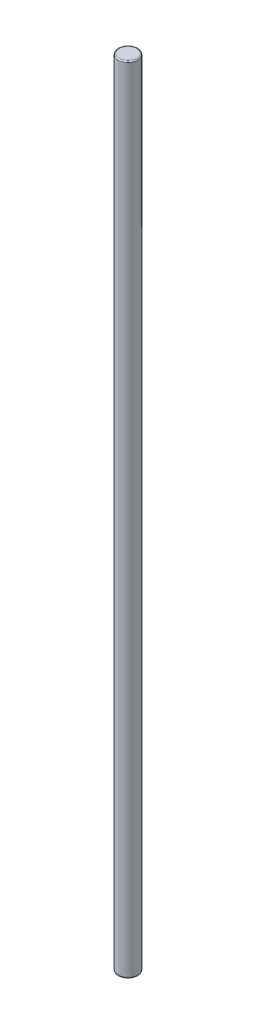
SolidWorks part; units mm, degrees
material "AISI 304"
ref_plane "Front Plane" through (0, 0, 0) normal (0, 0, 1) x (1, 0, 0)
ref_plane "Top Plane" through (0, 0, 0) normal (0, 1, 0) x (1, 0, 0)
ref_plane "Right Plane" through (0, 0, 0) normal (1, 0, 0) x (0, 0, -1)
sketch "Sketch1" plane through (0, 0, 0) normal (0, 1, 0) x (1, 0, 0)
  circle A0 centre (0, 0) radius 4
  dimension "D1" = 8
extrude "Boss-Extrude1" add sketch "Sketch1" along normal mid plane 325 contours A0
fillet "Fillet1" radius 0.5 2 edges at (0, -162.5, 4) (0, 162.5, 4)
